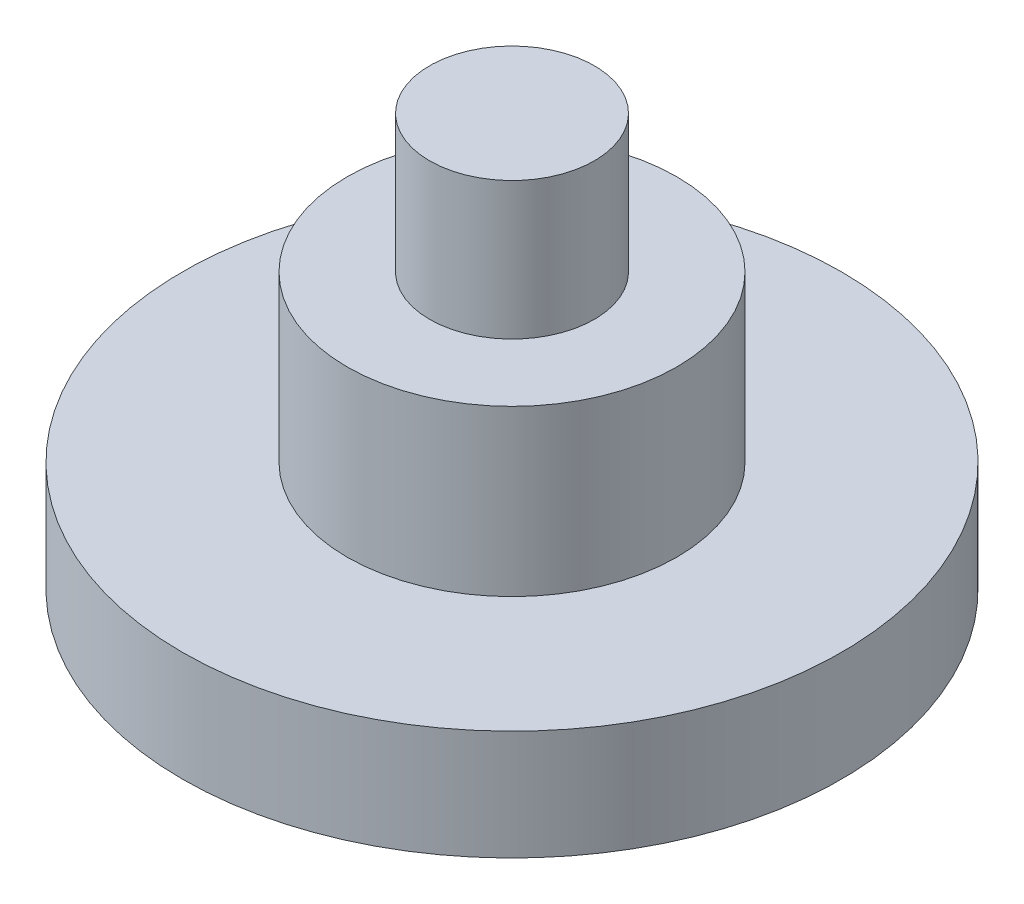
SolidWorks part; units mm, degrees
ref_plane "Front Plane" through (0, 0, 0) normal (0, 0, 1) x (1, 0, 0)
ref_plane "Top Plane" through (0, 0, 0) normal (0, 1, 0) x (1, 0, 0)
ref_plane "Right Plane" through (0, 0, 0) normal (1, 0, 0) x (0, 0, -1)
sketch "Sketch1" plane through (0, 0, 0) normal (0, 1, 0) x (1, 0, 0)
  circle A0 centre (0, 0) radius 60
extrude "Boss-Extrude1" add sketch "Sketch1" along normal blind 20
sketch "Sketch2" plane through (0, 20, 0) normal (0, 1, 0) x (1, 0, 0)
  circle A0 centre (0, 0) radius 30
extrude "Boss-Extrude2" add sketch "Sketch2" along normal blind 30
sketch "Sketch3" plane through (0, 50, 0) normal (0, 1, 0) x (1, 0, 0)
  circle A0 centre (0, 0) radius 15
extrude "Boss-Extrude3" add sketch "Sketch3" along normal blind 25
